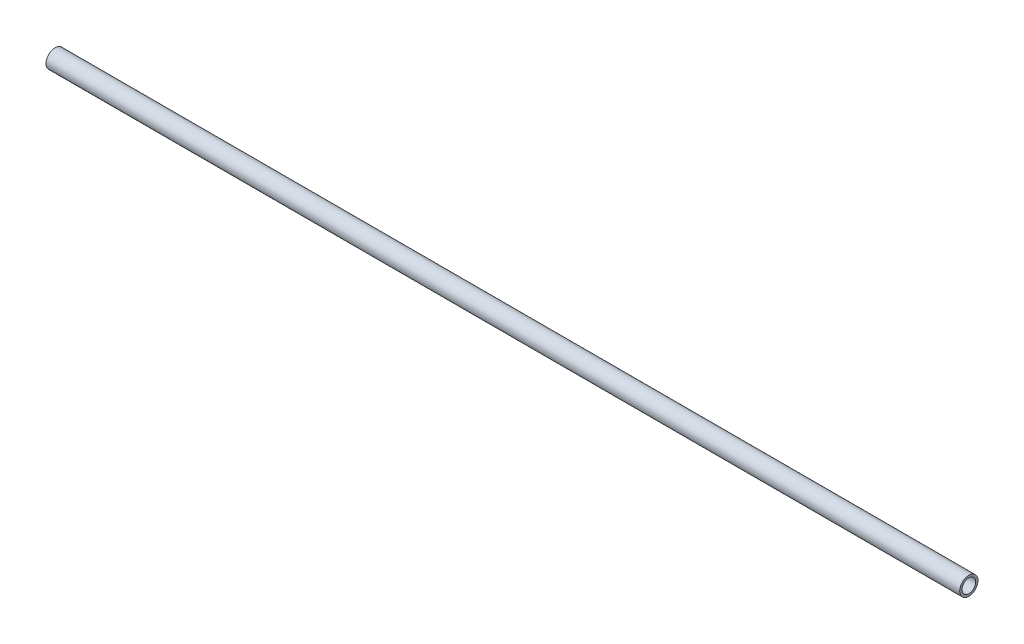
SolidWorks part; units mm, degrees
ref_plane "Front Plane" through (0, 0, 0) normal (0, 0, 1) x (1, 0, 0)
ref_plane "Top Plane" through (0, 0, 0) normal (0, 1, 0) x (1, 0, 0)
ref_plane "Right Plane" through (0, 0, 0) normal (1, 0, 0) x (0, 0, -1)
sketch "Sketch1" plane through (0, 0, 0) normal (1, 0, 0) x (0, 0, -1)
  circle A0 centre (0, 0) radius 1.5
  circle A1 centre (0, 0) radius 2
  dimension "D1" = 3
  dimension "D2" = 4
extrude "Boss-Extrude1" add sketch "Sketch1" along normal blind 200
